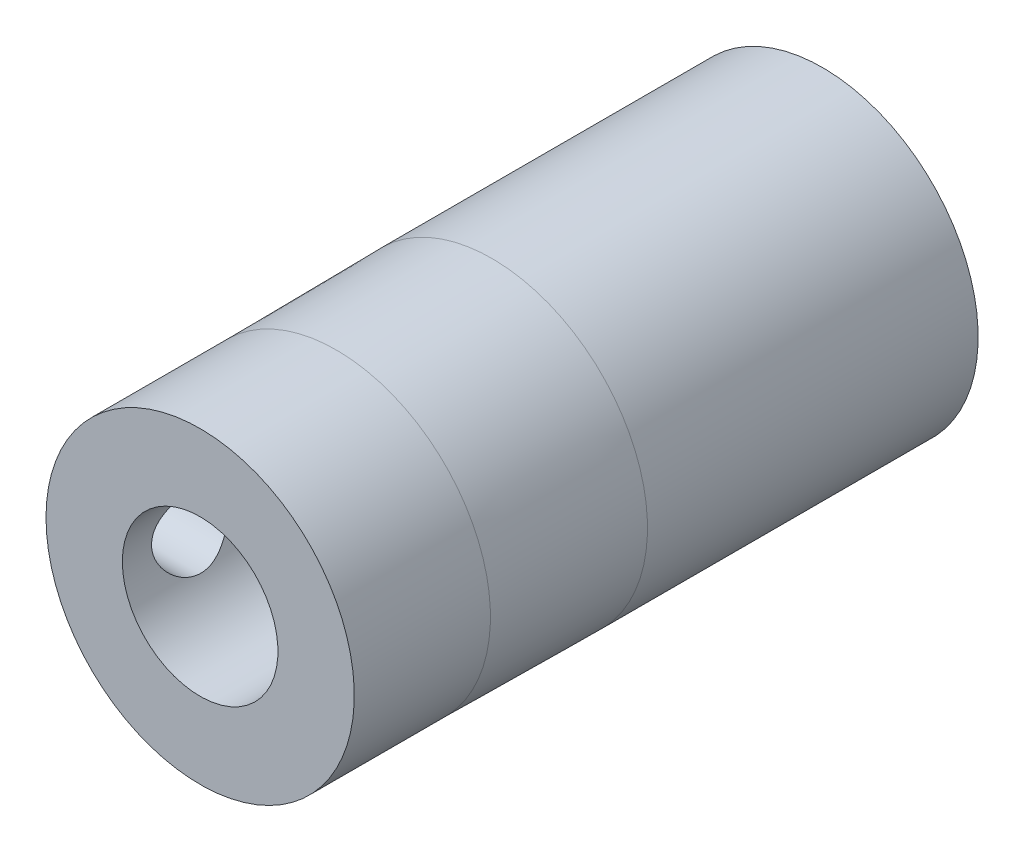
SolidWorks part; units mm, degrees
ref_plane "Piano frontale" through (0, 0, 0) normal (0, 0, 1) x (1, 0, 0)
ref_plane "Piano superiore" through (0, 0, 0) normal (0, 1, 0) x (1, 0, 0)
ref_plane "Piano destro" through (0, 0, 0) normal (1, 0, 0) x (0, 0, -1)
ref_axis "Assi1" through (0, 0, -88.99) along (0, 0, 1)
sketch "Schizzo1" plane through (0, 0, 0) normal (0, 1, 0) x (1, 0, 0)
  line L0 (4, 46.6742) -> (8, 46.6742)
  line L1 (8, 46.6742) -> (8, 29.6742)
  line L2 (8, 29.6742) -> (7.925, 21.6742)
  line L3 (7.925, 21.6742) -> (7.925, 14.6742)
  line L4 (7.925, 14.6742) -> (4, 14.6742)
  line L5 (4, 14.6742) -> (4, 46.6742)
  line L6 (0, 88.99) -> (0, -88.99) construction
  point P8 (8, 26.1576)
  point P9 (6.5543, 22.1063)
  dimension "D1" = 4
  dimension "D2" = 4
  dimension "D3" = 32
  dimension "D4" = 17
  dimension "D5" = 7
  dimension "D6" = 7.925
revolve "Rivoluzione1" add sketch "Schizzo1" angle 360 about axis through (0, 0, -88.99) along (0, 0, 1)
sketch "Schizzo2" plane through (0, 0, 0) normal (1, 0, 0) x (0, 0, -1)
  line L0 (14.6742, 4) -> (14.6742, -4) construction
  line L1 (88.99, 0) -> (-88.99, 0) construction
  circle A0 centre (18.1742, 0) radius 2
  point P4 (0, 0)
  dimension "D2" = 4
  dimension "D1" = 3.5
extrude "Taglio-Estrusione1" cut sketch "Schizzo2" against normal through all
